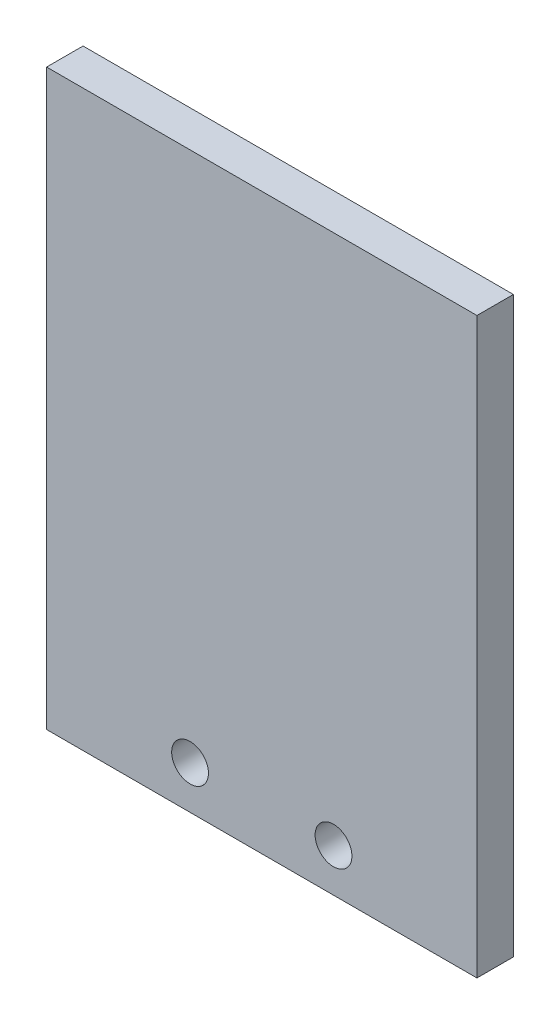
SolidWorks part; units mm, degrees
ref_plane "Front Plane" through (0, 0, 0) normal (0, 0, 1) x (1, 0, 0)
ref_plane "Top Plane" through (0, 0, 0) normal (0, 1, 0) x (1, 0, 0)
ref_plane "Right Plane" through (0, 0, 0) normal (1, 0, 0) x (0, 0, -1)
sketch "Sketch1" plane through (0, 0, 0) normal (0, 0, 1) x (1, 0, 0)
  line L1 (0, 0) -> (150, 0)
  line L2 (0, 0) -> (0, 200)
  line L3 (0, 200) -> (150, 200)
  line L4 (150, 0) -> (150, 200)
  dimension "D1" = 150
  dimension "D2" = 200
extrude "Boss-Extrude1" add sketch "Sketch1" along normal blind 12.7
hole_wizard "1/2 (0.5) Diameter Hole1" positions "Sketch5" profile "Sketch4" hole size "1/2" standard "ANSI Inch" end condition through all
sketch "Sketch5" plane through (0, 0, 12.7) normal (0, 0, 1) x (1, 0, 0)
  point P0 (100, 15)
  point P2 (50, 15)
  point P11 (0, 0)
  dimension "D1" = 50
  dimension "D3" = 50
  dimension "D4" = 15
sketch "Sketch4" plane through (100, 15, 12.7) normal (1, 0, 0) x (0, -1, 0)
  line L0 (0, 0) -> (0, 12.7)
  line L1 (0, 12.7) -> (6.4135, 12.7)
  line L2 (6.4135, 12.7) -> (6.4135, 0)
  line L5 (6.4135, 0) -> (0, 0)
  line L11 (0, -6.35) -> (0, 107.95) construction
  dimension "Thru Hole Dia." = 12.827
  dimension "Thru Hole Depth" = 12.7
equation "\"Plate_Height\"= 0.2m"
equation "\"Plate_Width\"= 0.1m"
equation "\"Plate_Thickness\"= 0.00635 * 2m"
